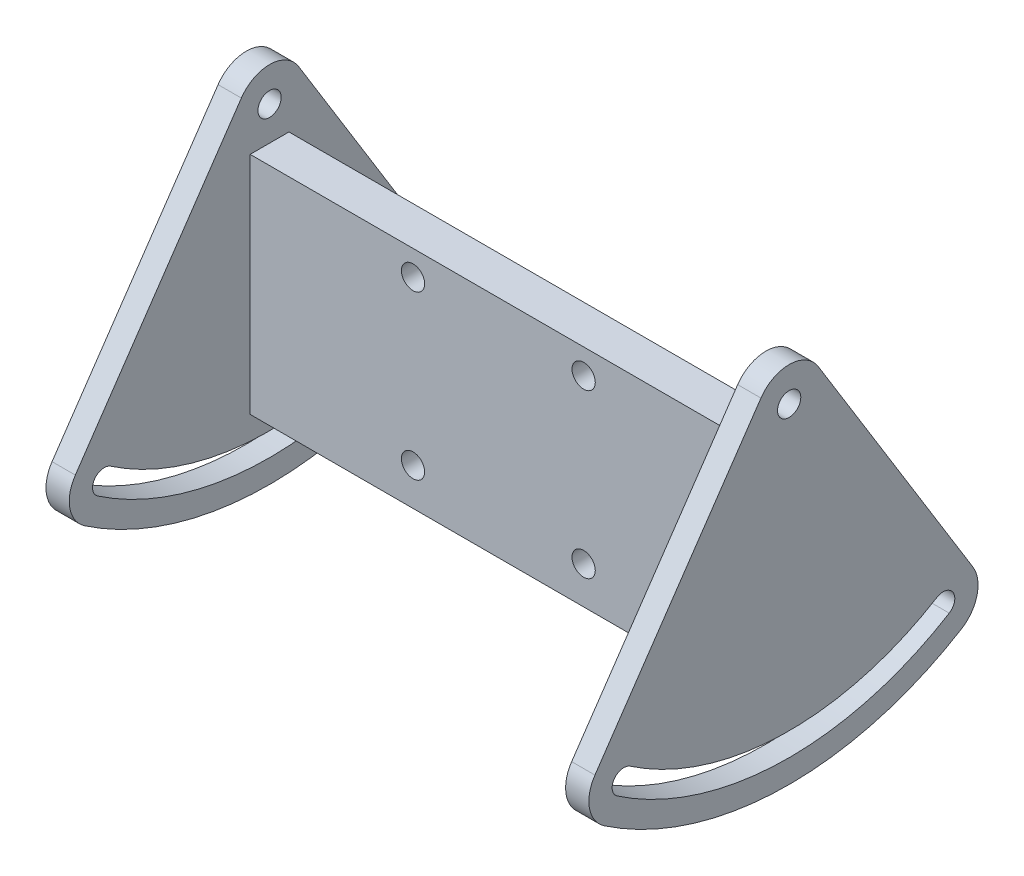
SolidWorks part; units mm, degrees
ref_plane "前视基准面" through (0, 0, 0) normal (0, 0, 1) x (1, 0, 0)
ref_plane "上视基准面" through (0, 0, 0) normal (0, 1, 0) x (1, 0, 0)
ref_plane "右视基准面" through (0, 0, 0) normal (1, 0, 0) x (0, 0, -1)
other "Configuration Table"
sketch "草图1" plane through (0, 0, 0) normal (1, 0, 0) x (0, 0, -1)
  line L0 (-3.6384, 14.0008) -> (-25.423, -17.952)
  line L1 (0, 11.5203) -> (-0.69, -18.4718) construction
  line L2 (3.7486, 13.8309) -> (24.0408, -19.09)
  arc A0 (3.7486, 13.8309) -> (-3.6384, 14.0008) centre (0, 11.5203) ccw
  circle A1 centre (0, 11.5203) radius 1.5
  arc A2 (-21.3261, -19.9312) -> (19.8572, -20.8787) centre (0, 11.5203) ccw construction
  arc A3 (-22.1679, -21.1728) -> (20.641, -22.1576) centre (0, 11.5203) ccw
  arc A4 (-20.4843, -18.6897) -> (19.0733, -19.5998) centre (0, 11.5203) ccw
  arc A5 (-20.4843, -18.6897) -> (-22.1679, -21.1728) centre (-21.3261, -19.9312) ccw
  arc A6 (20.641, -22.1576) -> (19.0733, -19.5998) centre (19.8572, -20.8787) ccw
  arc A7 (-23.8515, -23.6558) -> (22.2087, -24.7154) centre (0, 11.5203) ccw
  arc A8 (22.2087, -24.7154) -> (23.6879, -18.5175) centre (19.8572, -20.8787) ccw
  arc A10 (-25.0442, -17.3963) -> (-23.8515, -23.6558) centre (-21.3261, -19.9312) ccw
  arc A12 (-18.8006, -16.2067) -> (-23.8515, -23.6558) centre (-21.3261, -19.9312) ccw construction
  arc A13 (-18.8006, -16.2067) -> (17.5056, -17.042) centre (0, 11.5203) ccw construction
  arc A14 (22.2087, -24.7154) -> (17.5056, -17.042) centre (19.8572, -20.8787) ccw construction
  point P7 (-0.874, -26.4697)
  dimension "D1" = 3
  dimension "D2" = 3
  dimension "D4" = 38
  dimension "D3" = 3
extrude "凸台-拉伸1" add sketch "草图1" along normal blind 70 contours L0 A10 A7 A8 L2 A0 A1 A6 A3 A5 A4
sketch "草图3" plane through (0, 0, 0) normal (0, 1, 0) x (1, 0, 0)
  line L0 (0, 0) -> (40.3756, 0) construction
  line L1 (3, 2.5) -> (67, 2.5)
  line L2 (67, 2.5) -> (67, 32.5)
  line L3 (67, 32.5) -> (3, 32.5)
  line L4 (3, 32.5) -> (3, 2.5)
  line L5 (3, -2.5) -> (67, -2.5)
  line L6 (3, -32.5) -> (3, -2.5)
  line L7 (67, -2.5) -> (67, -32.5)
  line L8 (67, -32.5) -> (3, -32.5)
  line L9 (0, 3.7486) -> (0, 23.6879) construction
  line L10 (70, 3.7486) -> (70, 23.6879) construction
  dimension "D1" = 30
  dimension "D2" = 2.5
  dimension "D3" = 3
  dimension "D4" = 3
extrude "切除-拉伸1" cut sketch "草图3" against normal blind 48 and the other way blind 40
sketch "草图4" plane through (0, 0, 2.5) normal (0, 0, 1) x (1, 0, 0)
  line L0 (-8.7603, 0) -> (44.1649, 0) construction
  line L1 (24, 3.9238) -> (46, 3.9238) construction
  line L2 (24, 3.9238) -> (24, -17.0762) construction
  line L3 (24, -17.0762) -> (46, -17.0762) construction
  line L4 (46, 3.9238) -> (46, -17.0762) construction
  line L5 (35, 15.4662) -> (35, -28.166) construction
  line L8 (3, 14.0008) -> (3, -17.3963) construction
  line L9 (67, 15.1453) -> (67, -24.894) construction
  line L10 (70, 15.9238) -> (0, 15.9238) construction
  circle A0 centre (24, 3.9238) radius 1.5
  circle A1 centre (46, 3.9238) radius 1.5
  circle A2 centre (46, -17.0762) radius 1.5
  circle A3 centre (24, -17.0762) radius 1.5
  dimension "D3" = 3
  dimension "D1" = 22
  dimension "D2" = 21
  dimension "D4" = 12
extrude "切除-拉伸2" cut sketch "草图4" against normal blind 10
sketch "草图5" plane through (0, 0, 2.5) normal (0, 0, 1) x (1, 0, 0)
  line L1 (3, -21.894) -> (67, -21.894)
  line L2 (3, -21.894) -> (3, -31.894)
  line L3 (3, -31.894) -> (67, -31.894)
  line L4 (67, -21.894) -> (67, -31.894)
  line L5 (3, -24.894) -> (67, -24.894) construction
  line L6 (3, 14.0008) -> (3, -17.3963) construction
  line L7 (3, 20.1453) -> (67, 20.1453)
  line L8 (3, 20.1453) -> (3, 7.1453)
  line L9 (3, 7.1453) -> (67, 7.1453)
  line L10 (67, 20.1453) -> (67, 7.1453)
  line L11 (67, 15.1453) -> (67, -24.894) construction
  line L12 (67, 15.1453) -> (3, 15.1453) construction
  dimension "D1" = 10
  dimension "D2" = 7
  dimension "D3" = 8
  dimension "D4" = 5
extrude "切除-拉伸4" cut sketch "草图5" along normal blind 17 and the other way blind 11
